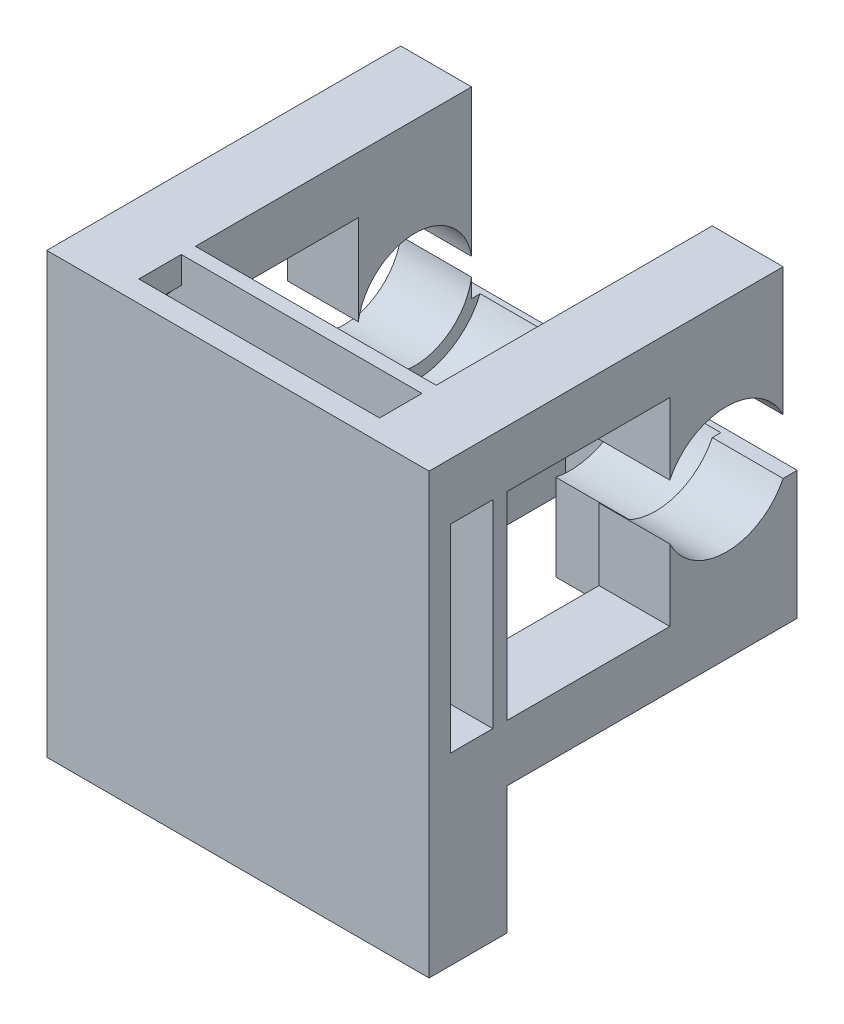
SolidWorks part; units mm, degrees
ref_plane "Front Plane" through (0, 0, 0) normal (0, 0, 1) x (1, 0, 0)
ref_plane "Top Plane" through (0, 0, 0) normal (0, 1, 0) x (1, 0, 0)
ref_plane "Right Plane" through (0, 0, 0) normal (1, 0, 0) x (0, 0, -1)
sketch "Sketch1" plane through (0, 0, 0) normal (0, 0, 1) x (1, 0, 0)
  line L1 (0, 0) -> (68.58, 0)
  line L2 (0, 0) -> (0, 55.88)
  line L3 (0, 55.88) -> (68.58, 55.88)
  line L4 (68.58, 0) -> (68.58, 55.88)
  dimension "D1" = 55.88
  dimension "D2" = 68.58
extrude "Boss-Extrude1" add sketch "Sketch1" along normal blind 3.81 contours L1 L4 L3 L2
sketch "Sketch2" plane through (0, 0, 0) normal (0, 0, -1) x (-1, 0, 0)
  line L0 (-12.7, 55.88) -> (-12.7, 45.72)
  line L1 (-68.58, 55.88) -> (-55.88, 55.88)
  line L2 (-68.58, 55.88) -> (-68.58, 45.72)
  line L3 (-68.58, 45.72) -> (-55.88, 45.72)
  line L4 (-55.88, 55.88) -> (-55.88, 45.72)
  line L5 (-12.7, 55.88) -> (0, 55.88)
  line L6 (0, 55.88) -> (0, 45.72)
  line L7 (-12.7, 45.72) -> (0, 45.72)
  line L8 (-12.7, 10.16) -> (-12.7, 0)
  line L9 (-12.7, 10.16) -> (0, 10.16)
  line L10 (0, 10.16) -> (0, 0)
  line L11 (-12.7, 0) -> (0, 0)
  line L12 (-68.58, 10.16) -> (-68.58, 0)
  line L13 (-68.58, 10.16) -> (-55.88, 10.16)
  line L14 (-55.88, 10.16) -> (-55.88, 0)
  line L15 (-68.58, 0) -> (-55.88, 0)
  line M5 (-68.58, 0) -> (0, 0)
  line M6 (0, 0) -> (0, 55.88)
  line M7 (0, 55.88) -> (-68.58, 55.88)
  line M8 (-68.58, 55.88) -> (-68.58, 0)
  dimension "D1" = 12.7
  dimension "D2" = 10.16
  dimension "D3" = 2
  dimension "D4" = 2
extrude "Boss-Extrude2" add sketch "Sketch2" along normal blind 59.69 contours L4 L3 M7 M8 | L0 L7 M6 M7 | L9 L8 M5 M6 | L14 L13 M8 M5
sketch "Sketch4" plane through (68.58, 0, 0) normal (1, 0, 0) x (0, 0, -1)
  line L0 (59.69, 55.88) -> (59.69, 45.72) construction
  circle A0 centre (49.53, 27.94) radius 11.303
  dimension "D1" = 22.606
  dimension "D2" = 10.16
sketch "Sketch6" plane through (0, 10.16, 0) normal (0, 1, 0) x (1, 0, 0)
  line L0 (68.58, 59.69) -> (68.58, 0) construction
  line L1 (55.88, 59.69) -> (68.58, 59.69)
  line L2 (55.88, 59.69) -> (55.88, 39.37)
  line L3 (55.88, 39.37) -> (68.58, 39.37)
  line L4 (68.58, 59.69) -> (68.58, 39.37)
  line L5 (0, 59.69) -> (0, 39.37)
  line L6 (0, 59.69) -> (12.7, 59.69)
  line L7 (12.7, 59.69) -> (12.7, 39.37)
  line L8 (0, 39.37) -> (12.7, 39.37)
  dimension "D1" = 20.32
  dimension "D2" = 2
extrude "Boss-Extrude3" add sketch "Sketch6" along normal blind 35.56
extrude "Cut-Extrude1" cut sketch "Sketch4" against normal up to next contours A0
ref_plane "Plane1" through (0, 0, -7.62) normal (0, 0, -1) x (-1, 0, 0)
sketch "Sketch7" plane through (0, 0, -7.62) normal (0, 0, -1) x (-1, 0, 0)
  line L1 (-68.58, 55.88) -> (0, 55.88)
  line L2 (-68.58, 55.88) -> (-68.58, 0)
  line L3 (-68.58, 0) -> (0, 0)
  line L4 (0, 55.88) -> (0, 0)
  line L5 (-55.88, 0) -> (-12.7, 0)
  line L6 (-55.88, 0) -> (-55.88, -22.86)
  line L7 (-55.88, -22.86) -> (-12.7, -22.86)
  line L8 (-12.7, 0) -> (-12.7, -22.86)
  dimension "D1" = 43.18
  dimension "D2" = 22.86
extrude "Boss-Extrude4" add sketch "Sketch7" along normal blind 2.54 contours L4 L1 L2 L3 | L8 L3 L6 L7
sketch "Sketch8" plane through (0, 0, -10.16) normal (0, 0, -1) x (-1, 0, 0)
  line L2 (-12.7, 0) -> (0, 0) construction
  line L3 (-68.58, 45.72) -> (-68.58, 10.16) construction
  circle A0 centre (-34.29, -10.16) radius 3.429
  circle A1 centre (-34.29, 27.94) radius 7.493
  dimension "D2" = 27.94
  dimension "D3" = 38.1
  dimension "D1" = 34.29
  dimension "D4" = 14.986
  dimension "D5" = 6.858
extrude "Cut-Extrude2" cut sketch "Sketch8" against normal blind 2.54 contours A0 | A1
sketch "Sketch9" plane through (0, 0, -59.69) normal (0, 0, -1) x (-1, 0, 0)
  line L1 (-68.58, 22.987) -> (0, 22.987)
  line L2 (-68.58, 22.987) -> (-68.58, 0)
  line L3 (-68.58, 0) -> (0, 0)
  line L4 (0, 22.987) -> (0, 0)
extrude "Boss-Extrude5" add sketch "Sketch9" along normal blind 2.54
ref_plane "Plane2" through (34.29, 0, 0) normal (-1, 0, 0) x (0, 0, 1)
sketch "Sketch10" plane through (0, 0, 0) normal (0, -1, 0) x (1, 0, 0)
  line L0 (55.88, -59.69) -> (12.7, -59.69) construction
  line L1 (28.067, -58.166) -> (40.513, -58.166)
  line L2 (28.067, -58.166) -> (28.067, -61.214)
  line L3 (28.067, -61.214) -> (40.513, -61.214)
  line L4 (40.513, -58.166) -> (40.513, -61.214)
  line L5 (28.067, -58.166) -> (40.513, -61.214) construction
  line L6 (28.067, -61.214) -> (40.513, -58.166) construction
  point P0 (34.29, -59.69)
  dimension "D1" = 1.524
  dimension "D2" = 12.446
extrude "Cut-Extrude3" cut sketch "Sketch10" against normal up to next
sketch "Sketch11" plane through (0, 0, -59.69) normal (0, 0, 1) x (1, 0, 0)
  line L1 (12.7, 22.987) -> (28.067, 22.987)
  line L2 (12.7, 22.987) -> (12.7, 0)
  line L3 (12.7, 0) -> (28.067, 0)
  line L4 (28.067, 22.987) -> (28.067, 0)
  line L5 (40.513, 22.987) -> (55.88, 22.987)
  line L6 (40.513, 22.987) -> (40.513, 0)
  line L7 (40.513, 0) -> (55.88, 0)
  line L8 (55.88, 22.987) -> (55.88, 0)
extrude "Boss-Extrude6" add sketch "Sketch11" along normal blind 12.7
sketch "Sketch12" plane through (0, 0, 0) normal (0, -1, 0) x (1, 0, 0)
  line L0 (12.7, -10.16) -> (0, -10.16)
  line L1 (0, 3.81) -> (0, -62.23) construction
  line L2 (0, -10.16) -> (0, 3.81)
  line L3 (0, 3.81) -> (68.58, 3.81)
  line L4 (68.58, 3.81) -> (68.58, -10.16)
  line L5 (68.58, 3.81) -> (68.58, -62.23) construction
  line L6 (68.58, -10.16) -> (55.88, -10.16)
  line L7 (55.88, -10.16) -> (55.88, 0)
  line L8 (55.88, 0) -> (12.7, 0)
  line L9 (12.7, 0) -> (12.7, -10.16)
extrude "Boss-Extrude7" add sketch "Sketch12" along normal up to surface (22.86 mm away) up to face at (34.29, -22.86, -8.89)
sketch "Sketch13" plane through (12.7, 0, 0) normal (1, 0, 0) x (0, 0, -1)
  circle A0 centre (49.53, 27.94) radius 10.287
  dimension "D1" = 20.574
sketch "Sketch14" plane through (55.88, 0, 0) normal (1, 0, 0) x (0, 0, -1)
  circle A0 centre (49.53, 27.94) radius 12.7
  dimension "D1" = 25.4
extrude "Cut-Extrude5" cut sketch "Sketch14" against normal up to surface (43.18 mm away) contours A0
extrude "Cut-Extrude6" cut sketch "Sketch13" against normal up to next
sketch "Sketch15" plane through (0, 0, 0) normal (0, 0, -1) x (-1, 0, 0)
  circle A0 centre (-34.29, 27.94) radius 31.6409
extrude "Cut-Extrude7" cut sketch "Sketch15" along normal up to surface (7.62 mm away) up to face at (30.861, -10.16, -7.62)
